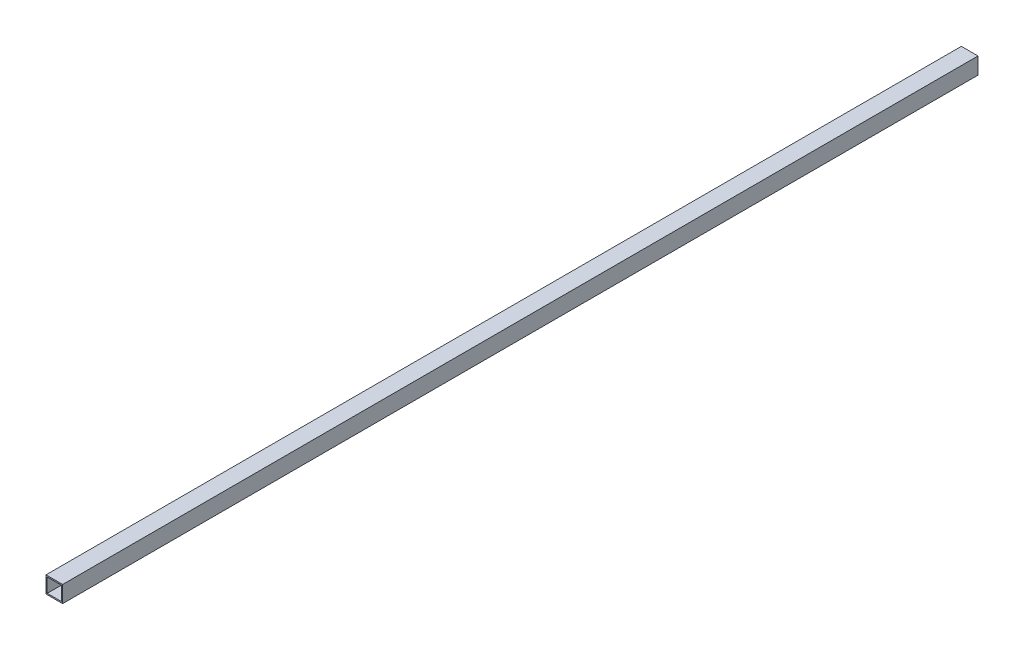
SolidWorks part; units mm, degrees
ref_plane "Front Plane" through (0, 0, 0) normal (0, 0, 1) x (1, 0, 0)
ref_plane "Top Plane" through (0, 0, 0) normal (0, 1, 0) x (1, 0, 0)
ref_plane "Right Plane" through (0, 0, 0) normal (1, 0, 0) x (0, 0, -1)
sketch "Sketch1" plane through (0, 0, 0) normal (0, 0, 1) x (1, 0, 0)
  line L1 (-20, 20) -> (20, 20)
  line L2 (-20, 20) -> (-20, -20)
  line L3 (-20, -20) -> (20, -20)
  line L4 (20, 20) -> (20, -20)
  line L5 (-20, 20) -> (20, -20) construction
  line L6 (-20, -20) -> (20, 20) construction
  point P0 (0, 0)
  dimension "D1" = 40
  dimension "D2" = 40
extrude "Boss-Extrude1" add sketch "Sketch1" along normal blind 2200
sketch "Sketch2" plane through (0, 0, 0) normal (0, 0, -1) x (-1, 0, 0)
  line L1 (-17, 17) -> (17, 17)
  line L2 (-17, 17) -> (-17, -17)
  line L3 (-17, -17) -> (17, -17)
  line L4 (17, 17) -> (17, -17)
  line L5 (-17, 17) -> (17, -17) construction
  line L6 (-17, -17) -> (17, 17) construction
  point P0 (0, 0)
  dimension "D1" = 34
  dimension "D2" = 34
extrude "Cut-Extrude1" cut sketch "Sketch2" against normal blind 2200
